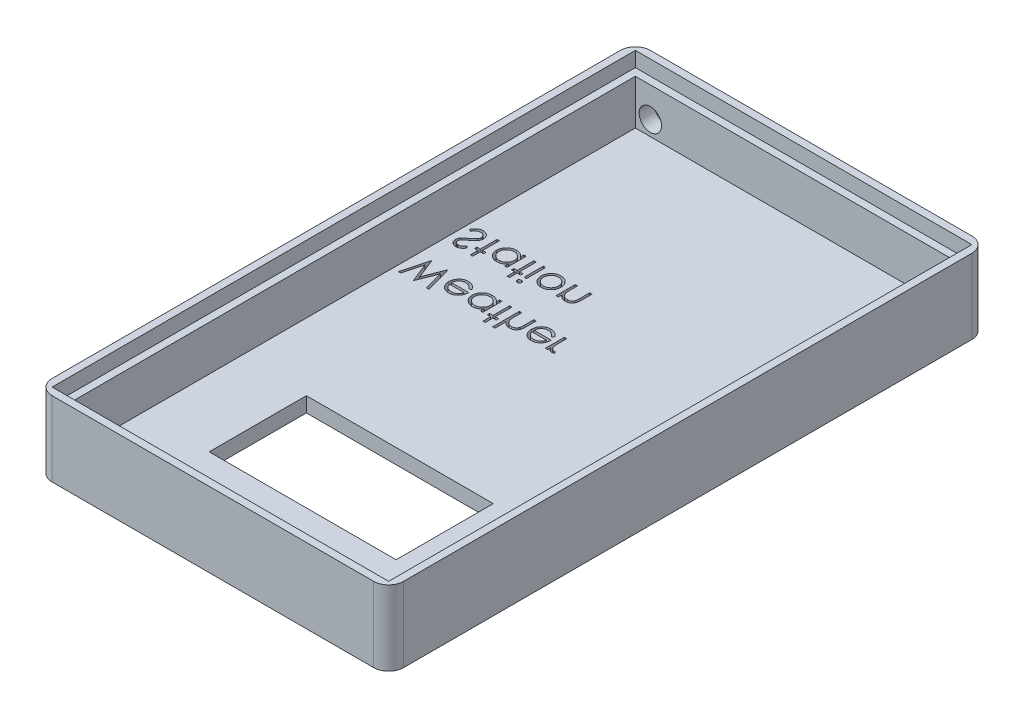
SolidWorks part; units mm, degrees
ref_plane "Front Plane" through (0, 0, 0) normal (0, 0, 1) x (1, 0, 0)
ref_plane "Top Plane" through (0, 0, 0) normal (0, 1, 0) x (1, 0, 0)
ref_plane "Right Plane" through (0, 0, 0) normal (1, 0, 0) x (0, 0, -1)
sketch "Sketch1" plane through (0, 0, 0) normal (0, 1, 0) x (1, 0, 0)
  line L1 (-23.5, 40) -> (23.5, 40)
  line L2 (-23.5, 40) -> (-23.5, -40)
  line L3 (-23.5, -40) -> (23.5, -40)
  line L4 (23.5, 40) -> (23.5, -40)
  line L5 (-23.5, 40) -> (23.5, -40) construction
  line L6 (-23.5, -40) -> (23.5, 40) construction
  point P0 (0, 0)
  dimension "D1" = 47
  dimension "D2" = 80
extrude "Boss-Extrude1" add sketch "Sketch1" along normal blind 10
sketch "Sketch2" plane through (0, 10, 0) normal (0, 1, 0) x (1, 0, 0)
  line L0 (23.5, 40) -> (-23.5, 40) construction
  line L1 (-21.5, 38) -> (21.5, 38)
  line L2 (-21.5, 38) -> (-21.5, -38)
  line L3 (-21.5, -38) -> (21.5, -38)
  line L4 (21.5, 38) -> (21.5, -38)
  line L5 (-21.5, 38) -> (21.5, -38) construction
  line L6 (-21.5, -38) -> (21.5, 38) construction
  line L8 (-23.5, 40) -> (-23.5, -40) construction
  point P0 (0, 0)
  dimension "D1" = 2
  dimension "D2" = 2
extrude "Cut-Extrude1" cut sketch "Sketch2" against normal blind 8
sketch "Sketch3" plane through (0, 2, 0) normal (0, 1, 0) x (1, 0, 0)
  line L0 (0, 38) -> (0, -38) construction
  line L1 (21.5, 38) -> (-21.5, 38) construction
  line L2 (-21.5, -38) -> (21.5, -38) construction
  line L3 (-21.5, -38) -> (21.5, -38) construction
  line L4 (-12.5, -15) -> (12.5, -15)
  line L5 (-12.5, -15) -> (-12.5, -28)
  line L6 (-12.5, -28) -> (12.5, -28)
  line L7 (12.5, -15) -> (12.5, -28)
  line L8 (-12.5, -15) -> (12.5, -28) construction
  line L9 (-12.5, -28) -> (12.5, -15) construction
  point P6 (0, -21.5)
  point P11 (0, -20.7414)
  dimension "D1" = 13
  dimension "D2" = 25
  dimension "D3" = 10
extrude "Cut-Extrude2" cut sketch "Sketch3" against normal blind 6
sketch "Sketch4" plane through (0, 10, 0) normal (0, 1, 0) x (1, 0, 0)
  line L0 (-22.5, 39) -> (22.5, 39)
  line L1 (22.5, 39) -> (22.5, -39)
  line L3 (22.5, -39) -> (-22.5, -39)
  line L4 (-22.5, -39) -> (-22.5, 39)
  line L6 (-23.5, -40) -> (23.5, -40) construction
  line L7 (23.5, -40) -> (23.5, 40) construction
  line L10 (23.5, 40) -> (-23.5, 40) construction
  line L12 (-21.5, 38) -> (-21.5, -38) construction
  line L13 (21.5, 38) -> (-21.5, 38) construction
  line L14 (21.5, -38) -> (21.5, 38) construction
  line L15 (-21.5, -38) -> (21.5, -38) construction
  line L16 (21.5, 38) -> (-21.5, 38)
  line L17 (21.5, -38) -> (21.5, 38)
  line L18 (-21.5, -38) -> (21.5, -38)
  line L19 (-21.5, 38) -> (-21.5, -38)
  dimension "D1" = 1
  dimension "D2" = 1
  dimension "D3" = 1
  dimension "D4" = 1
extrude "Cut-Extrude3" cut sketch "Sketch4" against normal blind 2
sketch "Sketch6" plane through (0, 0, 0) normal (0, -1, 0) x (1, 0, 0)
  text T0 "Weather\r\nStation"
  point P1 (0, 0)
  point P2 (-20.5911, -4.5885)
  point P3 (-20.9488, -9.0154)
extrude "Cut-Extrude6" cut sketch "Sketch6" against normal blind 2
sketch "Sketch7" plane through (0, 0, -40) normal (0, 0, -1) x (-1, 0, 0)
  line L0 (-23.5, 0) -> (23.5, 0) construction
  line L1 (-23.5, 10) -> (-23.5, 0) construction
  line L2 (0, 5.5) -> (0, -5.5) construction
  circle A0 centre (-19.5, 4) radius 1.5
  circle A1 centre (19.5, 4) radius 1.5
  dimension "D1" = 3
  dimension "D2" = 4
  dimension "D3" = 4
extrude "Cut-Extrude7" cut sketch "Sketch7" against normal blind 5
fillet "Fillet2" radius 2 4 edges at (-23.5, 5, 40) (23.5, 5, 40) (23.5, 5, -40) (-23.5, 5, -40)
